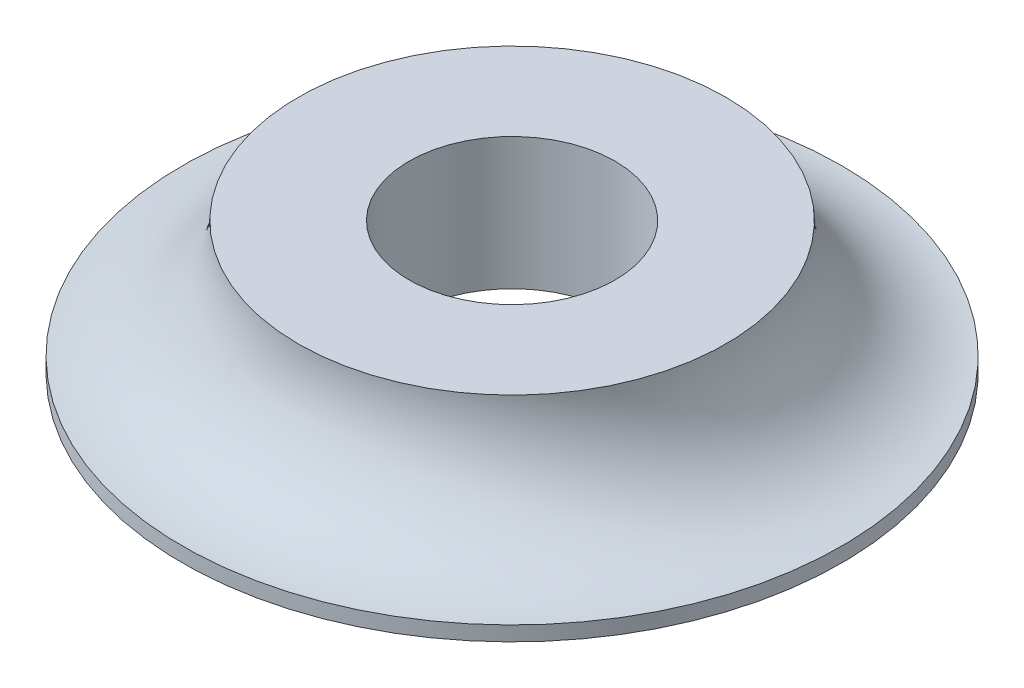
SolidWorks part; units mm, degrees
ref_plane "Front Plane" through (0, 0, 0) normal (0, 0, 1) x (1, 0, 0)
ref_plane "Top Plane" through (0, 0, 0) normal (0, 1, 0) x (1, 0, 0)
ref_plane "Right Plane" through (0, 0, 0) normal (1, 0, 0) x (0, 0, -1)
sketch "Sketch3" plane through (0, 0, 0) normal (0, 0, 1) x (1, 0, 0)
  line L0 (3.9688, 0) -> (12.7, 0)
  line L1 (3.9688, 5.08) -> (3.9688, 0)
  line L2 (12.7, 0) -> (12.7, 0.5657)
  line L3 (0, 0) -> (0, 6.9881) construction
  line L5 (3.9688, 5.08) -> (8.237, 5.08)
  arc A0 (12.7, 0.5657) -> (8.237, 5.08) centre (12.7257, 5.0543) cw
  dimension "D1" = 4.2683
  dimension "D2" = 5.08
revolve "Revolve1" add sketch "Sketch3" angle 360 about L3
